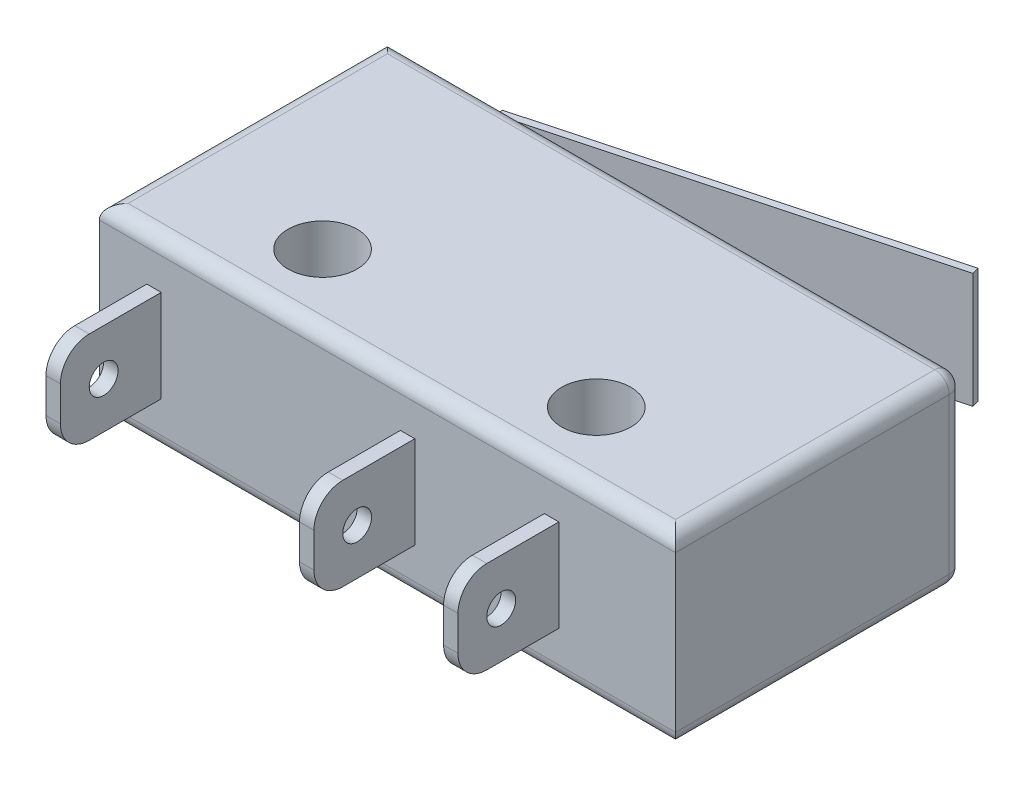
SolidWorks part; units mm, degrees
ref_plane "Front Plane" through (0, 0, 0) normal (0, 0, 1) x (1, 0, 0)
ref_plane "Top Plane" through (0, 0, 0) normal (0, 1, 0) x (1, 0, 0)
ref_plane "Right Plane" through (0, 0, 0) normal (1, 0, 0) x (0, 0, -1)
sketch "Sketch1" plane through (0, 0, 0) normal (0, 1, 0) x (1, 0, 0)
  line L0 (5.25, 2.5) -> (14.75, 2.5) construction
  line L1 (0, 0) -> (20, 0)
  line L2 (0, 0) -> (0, 10)
  line L3 (0, 10) -> (20, 10)
  line L4 (20, 0) -> (20, 10)
  circle A0 centre (5.25, 2.5) radius 1.2
  circle A1 centre (14.75, 2.5) radius 1.2
  dimension "D5" = 2.4
  dimension "D1" = 20
  dimension "D2" = 10
  dimension "D3" = 9.5
  dimension "D4" = 5.25
  dimension "D6" = 2.5
extrude "Boss-Extrude1" add sketch "Sketch1" along normal blind 6.4
sketch "Sketch2" plane through (0, 0, 0) normal (0, 0, 1) x (1, 0, 0)
  line L0 (1.9, 6.4) -> (1.9, 0) construction
  line L1 (0, 6.4) -> (20, 6.4) construction
  line L2 (0, 0) -> (20, 0) construction
  line L3 (10.7, 6.4) -> (10.7, 0) construction
  line L4 (15.7, 6.4) -> (15.7, 0) construction
  line L5 (0, 6.4) -> (0, 0) construction
  line L6 (15.95, 4.8) -> (15.45, 4.8)
  line L7 (15.95, 4.8) -> (15.95, 1.6)
  line L8 (15.95, 1.6) -> (15.45, 1.6)
  line L9 (15.45, 4.8) -> (15.45, 1.6)
  line L10 (15.95, 4.8) -> (15.45, 1.6) construction
  line L11 (15.95, 1.6) -> (15.45, 4.8) construction
  line L12 (10.45, 4.8) -> (10.95, 4.8)
  line L13 (10.45, 4.8) -> (10.45, 1.6)
  line L14 (10.45, 1.6) -> (10.95, 1.6)
  line L15 (10.95, 4.8) -> (10.95, 1.6)
  line L16 (10.45, 4.8) -> (10.95, 1.6) construction
  line L17 (10.45, 1.6) -> (10.95, 4.8) construction
  line L18 (1.65, 4.8) -> (2.15, 4.8)
  line L19 (1.65, 4.8) -> (1.65, 1.6)
  line L20 (1.65, 1.6) -> (2.15, 1.6)
  line L21 (2.15, 4.8) -> (2.15, 1.6)
  line L22 (1.65, 4.8) -> (2.15, 1.6) construction
  line L23 (1.65, 1.6) -> (2.15, 4.8) construction
  point P10 (15.7, 3.2)
  point P15 (10.7, 3.2)
  point P20 (1.9, 3.2)
  dimension "D1" = 1.9
  dimension "D2" = 8.8
  dimension "D3" = 5
  dimension "D4" = 3.2
  dimension "D5" = 0.5
extrude "Boss-Extrude2" add sketch "Sketch2" along normal blind 3.5
sketch "Sketch3" plane through (1.65, 0, 0) normal (-1, 0, 0) x (0, 0, 1)
  line L0 (3.5, 3.2) -> (0, 3.2) construction
  line L1 (3.5, 4.8) -> (3.5, 1.6) construction
  line L2 (0, 4.8) -> (0, 1.6) construction
  circle A0 centre (2, 3.2) radius 0.5
  dimension "D1" = 1
  dimension "D2" = 1.5
extrude "Cut-Extrude1" cut sketch "Sketch3" against normal through all
fillet "Fillet1" radius 1 6 edges at (15.7, 1.6, 3.5) (15.7, 4.8, 3.5) (10.7, 4.8, 3.5) (10.7, 1.6, 3.5) (1.9, 1.6, 3.5) (1.9, 4.8, 3.5)
fillet "Fillet2" radius 0.5 9 edges at (10, 0, -10) (10, 6.4, -10) (20, 3.2, -10) (20, 0, -5) (20, 6.4, -5) (0, 0, -5) (0, 6.4, -5) (10, 0, 0) (10, 6.4, 0)
ref_plane "Plane1" through (0, 3.2, 0) normal (0, 1, 0) x (1, 0, 0)
sketch "Sketch4" plane through (0, 3.2, 0) normal (0, 1, 0) x (1, 0, 0)
  line L0 (3, 10) -> (3, 11)
  line L1 (0, 10) -> (19.5, 10) construction
  line L2 (3, 11) -> (16, 14.5)
  line L3 (0, 0) -> (0, 10) construction
  circle A0 centre (14.75, 2.5) radius 1.2 construction
  dimension "D2" = 12
  dimension "D1" = 13
  dimension "D3" = 1
  dimension "D4" = 3
extrude "Extrude-Thin2" add sketch "Sketch4" against normal blind 2 and the other way blind 2 thin
sketch "Sketch5" plane through (0, 3.2, 0) normal (0, 1, 0) x (1, 0, 0)
  line L0 (4.75, 10) -> (4.75, 10.6375)
  line L1 (6.25, 10.6375) -> (6.25, 10)
  line L2 (0, 10) -> (19.5, 10) construction
  line L3 (3.25, 10.8084) -> (16.065, 14.2586) construction
  line L4 (3.25, 10) -> (3.25, 10.8084) construction
  line L5 (6.25, 10) -> (4.75, 10)
  arc A0 (4.75, 10.6375) -> (6.25, 10.6375) centre (5.5, 10.6375) cw
  point P9 (3.25, 10.4042)
  dimension "D1" = 1.5
  dimension "D2" = 1.5
extrude "Boss-Extrude6" add sketch "Sketch5" along normal blind 0.5 and the other way blind 0.5 separate body
